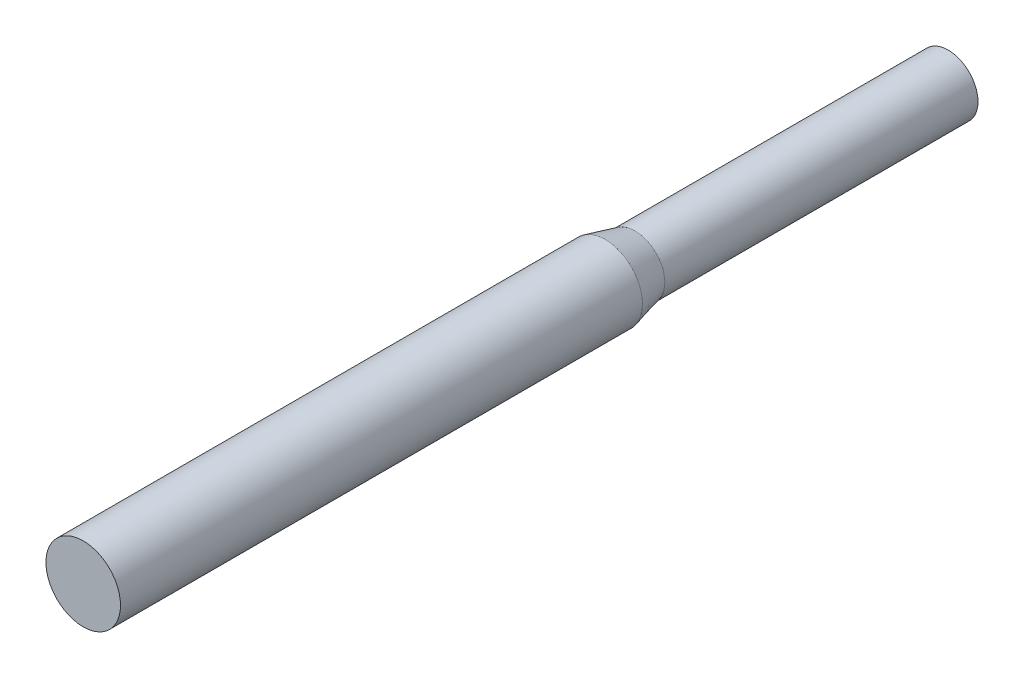
SolidWorks part; units mm, degrees
ref_plane "Front Plane" through (0, 0, 0) normal (0, 0, 1) x (1, 0, 0)
ref_plane "Top Plane" through (0, 0, 0) normal (0, 1, 0) x (1, 0, 0)
ref_plane "Right Plane" through (0, 0, 0) normal (1, 0, 0) x (0, 0, -1)
sketch "Sketch1" plane through (0, 0, 0) normal (0, 0, 1) x (1, 0, 0)
  circle A0 centre (0, 0) radius 2
  dimension "D1" = 4
extrude "Boss-Extrude1" add sketch "Sketch1" along normal blind 23
sketch "Sketch3" plane through (0, 0, 23) normal (0, 0, 1) x (1, 0, 0)
  circle A0 centre (0, 0) radius 2.5
  dimension "D1" = 5
extrude "Boss-Extrude3" add sketch "Sketch3" along normal blind 35
chamfer "Chamfer1" distance 2 angle 14 1 edges at (2, 0, 23)
